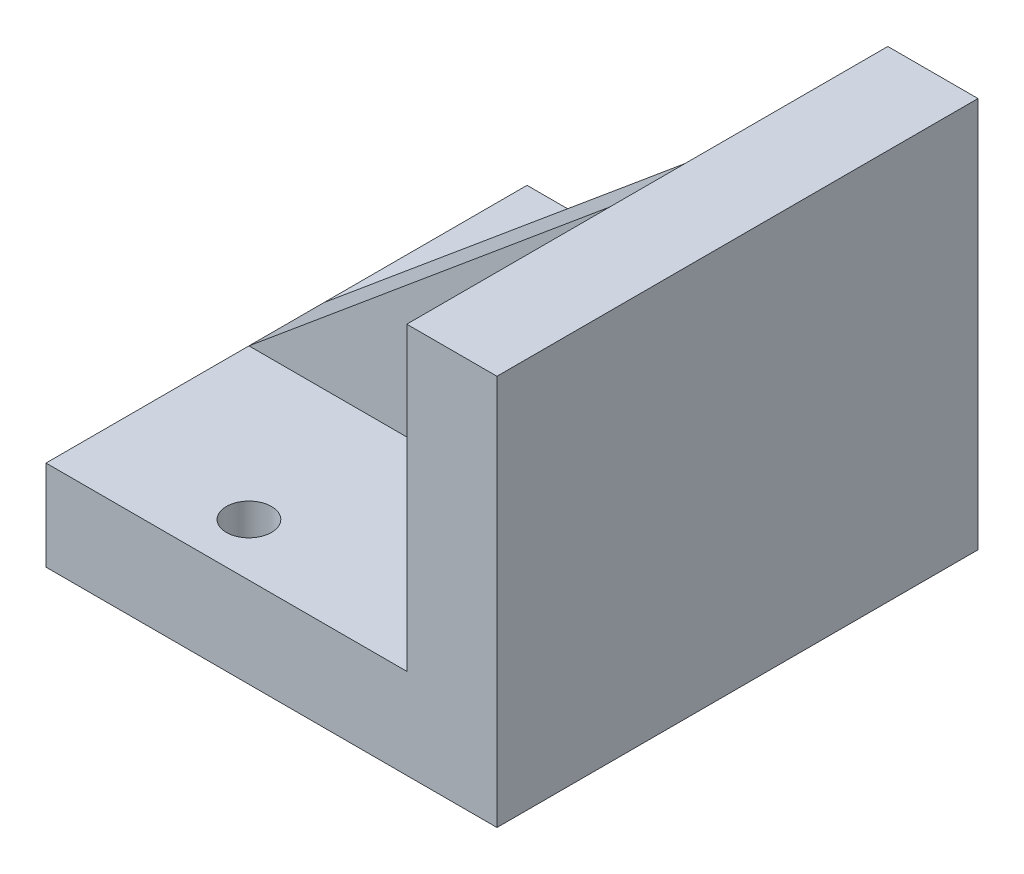
SolidWorks part; units mm, degrees
material "ABS"
ref_plane "前视基准面" through (0, 0, 0) normal (0, 0, 1) x (1, 0, 0)
ref_plane "上视基准面" through (0, 0, 0) normal (0, 1, 0) x (1, 0, 0)
ref_plane "右视基准面" through (0, 0, 0) normal (1, 0, 0) x (0, 0, -1)
sketch "草图1" plane through (0, 0, 0) normal (0, 1, 0) x (1, 0, 0)
  line L1 (-15, -16) -> (15, -16)
  line L2 (-15, -16) -> (-15, 16)
  line L3 (-15, 16) -> (15, 16)
  line L4 (15, -16) -> (15, 16)
  line L5 (-15, -16) -> (15, 16) construction
  line L6 (-15, 16) -> (15, -16) construction
  point P0 (0, 0)
  dimension "D1" = 30
  dimension "D2" = 32
extrude "凸台-拉伸1" add sketch "草图1" along normal blind 6
sketch "草图2" plane through (0, 6, 0) normal (0, 1, 0) x (1, 0, 0)
  line L0 (-15, -16) -> (15, -16) construction
  line L1 (15, 16) -> (9, 16)
  line L2 (15, 16) -> (15, -16)
  line L3 (15, -16) -> (9, -16)
  line L4 (9, 16) -> (9, -16)
  dimension "D1" = 6
extrude "凸台-拉伸2" add sketch "草图2" along normal blind 20
sketch "草图4" plane through (0, 6, 0) normal (0, 1, 0) x (1, 0, 0)
  line L0 (-5, 16) -> (-5, -16) construction
  line L1 (9, 16) -> (-15, 16) construction
  line L2 (-15, -16) -> (9, -16) construction
  line L3 (-15, 16) -> (-15, -16) construction
  line L4 (-5, 0) -> (-15, 0) construction
  circle A0 centre (-5, 12.5) radius 1.5
  circle A1 centre (-5, -12.5) radius 1.5
  dimension "D2" = 25
  dimension "D3" = 3
  dimension "D1" = 10
extrude "切除-拉伸1" cut sketch "草图4" against normal through all
sketch "草图5" plane through (0, 6, 0) normal (0, 1, 0) x (1, 0, 0)
  line L0 (-15, 0) -> (9, 0) construction
  line L1 (-15, 16) -> (-15, -16) construction
  line L2 (9, 16) -> (9, -16) construction
  line L4 (-15, -2.5) -> (9, -2.5)
  line L5 (-15, -2.5) -> (-15, 2.5)
  line L6 (-15, 2.5) -> (9, 2.5)
  line L7 (9, -2.5) -> (9, 2.5)
  line L8 (-15, -2.5) -> (9, 2.5) construction
  line L9 (-15, 2.5) -> (9, -2.5) construction
  point P6 (-3, 0)
  dimension "D1" = 5
extrude "凸台-拉伸3" add sketch "草图5" along normal through all
sketch "草图6" plane through (0, 0, 2.5) normal (0, 0, 1) x (1, 0, 0)
  line L0 (-15, 6) -> (-15, 26)
  line L1 (-15, 26) -> (9, 26)
  line L2 (9, 26) -> (-15, 6)
extrude "切除-拉伸2" cut sketch "草图6" against normal through all
